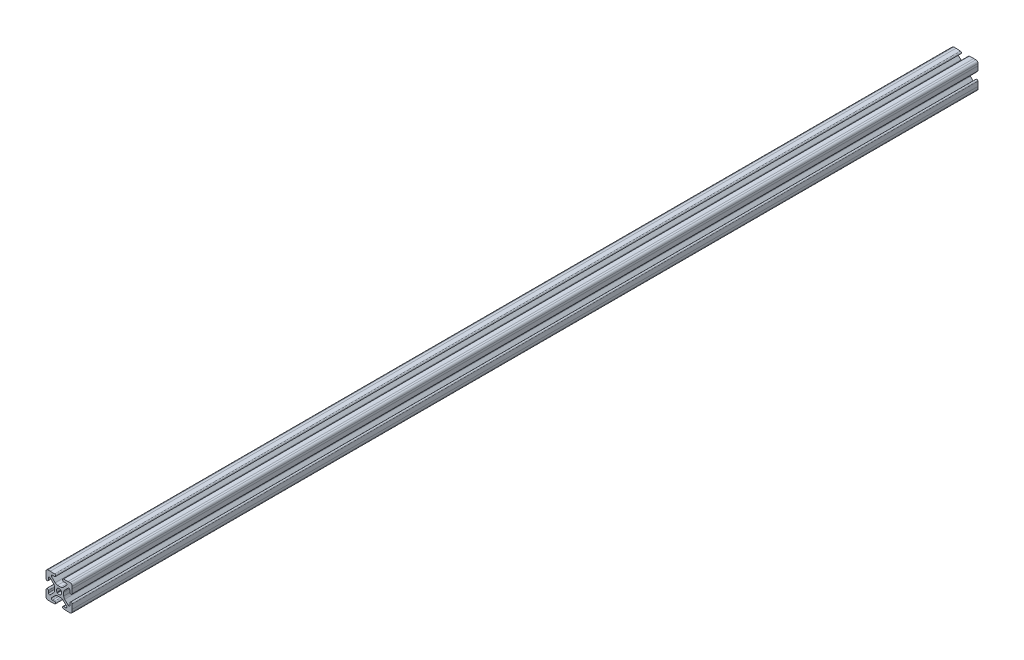
SolidWorks part; units mm, degrees
ref_plane "Front Plane" through (0, 0, 0) normal (0, 0, 1) x (1, 0, 0)
ref_plane "Top Plane" through (0, 0, 0) normal (0, 1, 0) x (1, 0, 0)
ref_plane "Right Plane" through (0, 0, 0) normal (1, 0, 0) x (0, 0, -1)
sketch "Model" plane through (0, 0, 0) normal (0, 0, 1) x (1, 0, 0)
  line L38 (50.6495, 75.4336) -> (50.2699, 75.4336)
  line L39 (50.2699, 75.4336) -> (50.2699, 75.8133)
  line L40 (50.66, 72.9999) -> (53.7746, 72.9999)
  line L41 (56.0196, 72.0699) -> (59.2642, 68.8254)
  line L42 (58.5103, 67.0916) -> (56.5725, 67.1592)
  line L43 (56.498, 65.0269) -> (60.6773, 64.881)
  line L44 (60.6773, 64.881) -> (62.7107, 64.881)
  line L45 (64.7173, 66.8876) -> (64.7173, 68.921)
  line L46 (64.7173, 68.921) -> (64.5713, 73.1002)
  line L47 (62.439, 73.0257) -> (62.5067, 71.0879)
  line L48 (60.7729, 70.334) -> (57.5283, 73.5786)
  line L49 (56.5984, 75.8237) -> (56.5984, 78.9383)
  line L50 (57.5283, 81.1833) -> (60.7729, 84.4279)
  line L51 (62.5067, 83.674) -> (62.439, 81.7362)
  line L52 (64.5713, 81.6617) -> (64.7173, 85.841)
  line L53 (64.7173, 85.841) -> (64.7173, 87.8744)
  line L54 (62.7107, 89.881) -> (60.6773, 89.881)
  line L55 (60.6773, 89.881) -> (56.498, 89.735)
  line L56 (56.5725, 87.6027) -> (58.5103, 87.6704)
  line L57 (59.2642, 85.9366) -> (56.0196, 82.692)
  line L58 (53.7746, 81.7621) -> (50.66, 81.7621)
  line L59 (48.4149, 82.692) -> (45.1703, 85.9366)
  line L60 (45.9242, 87.6704) -> (47.862, 87.6027)
  line L61 (47.9365, 89.735) -> (43.7573, 89.881)
  line L62 (43.7573, 89.881) -> (41.7239, 89.881)
  line L63 (39.7173, 87.8744) -> (39.7173, 85.841)
  line L64 (39.7173, 85.841) -> (39.8632, 81.6617)
  line L65 (41.9955, 81.7362) -> (41.9278, 83.674)
  line L66 (43.6616, 84.4279) -> (46.9062, 81.1833)
  line L67 (47.8361, 78.9383) -> (47.8361, 75.8237)
  line L68 (46.9062, 73.5786) -> (43.6616, 70.334)
  line L69 (41.9278, 71.0879) -> (41.9955, 73.0257)
  line L70 (39.8632, 73.1002) -> (39.7173, 68.921)
  line L71 (39.7173, 68.921) -> (39.7173, 66.8876)
  line L72 (41.7239, 64.881) -> (43.7573, 64.881)
  line L73 (43.7573, 64.881) -> (47.9365, 65.0269)
  line L74 (47.862, 67.1592) -> (45.9242, 67.0916)
  line L75 (45.1703, 68.8254) -> (48.4149, 72.0699)
  arc A29 (50.6495, 75.4336) -> (50.2699, 75.8133) centre (52.2173, 77.381) ccw
  arc A30 (56.0196, 72.0699) -> (53.7746, 72.9999) centre (53.7746, 69.8249) ccw
  arc A31 (58.5103, 67.0916) -> (59.2642, 68.8254) centre (58.5458, 68.1069) ccw
  arc A32 (56.5725, 67.1592) -> (56.498, 65.0269) centre (56.5353, 66.0931) ccw
  arc A33 (62.7107, 64.881) -> (64.7173, 66.8876) centre (62.7107, 66.8876) ccw
  arc A34 (64.5713, 73.1002) -> (62.439, 73.0257) centre (63.5052, 73.063) ccw
  arc A35 (60.7729, 70.334) -> (62.5067, 71.0879) centre (61.4913, 71.0525) ccw
  arc A36 (56.5984, 75.8237) -> (57.5283, 73.5786) centre (59.7734, 75.8237) ccw
  arc A37 (57.5283, 81.1833) -> (56.5984, 78.9383) centre (59.7734, 78.9383) ccw
  arc A38 (62.5067, 83.674) -> (60.7729, 84.4279) centre (61.4913, 83.7095) ccw
  arc A39 (62.439, 81.7362) -> (64.5713, 81.6617) centre (63.5052, 81.699) ccw
  arc A40 (64.7173, 87.8744) -> (62.7107, 89.881) centre (62.7107, 87.8744) ccw
  arc A41 (56.498, 89.735) -> (56.5725, 87.6027) centre (56.5353, 88.6689) ccw
  arc A42 (59.2642, 85.9366) -> (58.5103, 87.6704) centre (58.5458, 86.655) ccw
  arc A43 (53.7746, 81.7621) -> (56.0196, 82.692) centre (53.7746, 84.9371) ccw
  arc A44 (48.4149, 82.692) -> (50.66, 81.7621) centre (50.66, 84.9371) ccw
  arc A45 (45.9242, 87.6704) -> (45.1703, 85.9366) centre (45.8887, 86.655) ccw
  arc A46 (47.862, 87.6027) -> (47.9365, 89.735) centre (47.8993, 88.6689) ccw
  arc A47 (41.7239, 89.881) -> (39.7173, 87.8744) centre (41.7239, 87.8744) ccw
  arc A48 (39.8632, 81.6617) -> (41.9955, 81.7362) centre (40.9293, 81.699) ccw
  arc A49 (43.6616, 84.4279) -> (41.9278, 83.674) centre (42.9432, 83.7095) ccw
  arc A50 (47.8361, 78.9383) -> (46.9062, 81.1833) centre (44.6611, 78.9383) ccw
  arc A51 (46.9062, 73.5786) -> (47.8361, 75.8237) centre (44.6611, 75.8237) ccw
  arc A52 (41.9278, 71.0879) -> (43.6616, 70.334) centre (42.9432, 71.0525) ccw
  arc A53 (41.9955, 73.0257) -> (39.8632, 73.1002) centre (40.9293, 73.063) ccw
  arc A54 (39.7173, 66.8876) -> (41.7239, 64.881) centre (41.7239, 66.8876) ccw
  arc A55 (47.9365, 65.0269) -> (47.862, 67.1592) centre (47.8993, 66.0931) ccw
  arc A56 (45.1703, 68.8254) -> (45.9242, 67.0916) centre (45.8887, 68.1069) ccw
  arc A57 (50.66, 72.9999) -> (48.4149, 72.0699) centre (50.66, 69.8249) ccw
extrude "Boss-Extrude1" add sketch "Model" along normal blind 863.6
